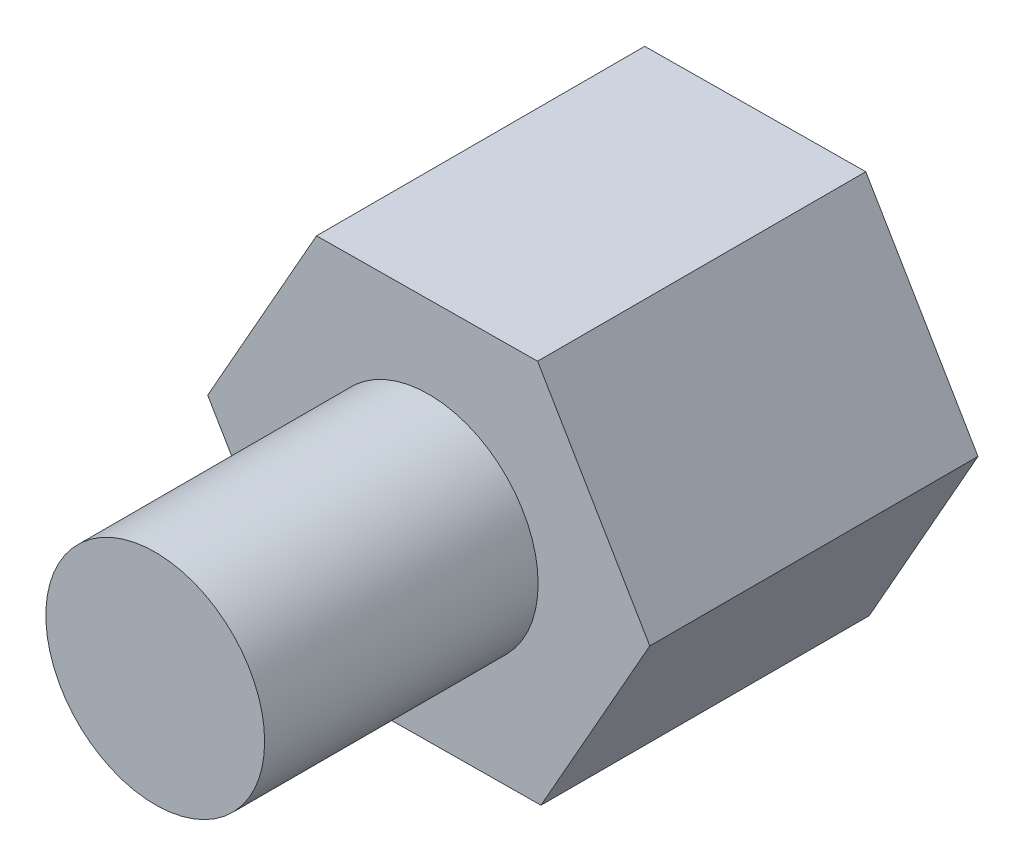
SolidWorks part; units mm, degrees
ref_plane "前视基准面" through (0, 0, 0) normal (0, 0, 1) x (1, 0, 0)
ref_plane "上视基准面" through (0, 0, 0) normal (0, 1, 0) x (1, 0, 0)
ref_plane "右视基准面" through (0, 0, 0) normal (1, 0, 0) x (0, 0, -1)
sketch "草图1" plane through (0, 0, 0) normal (0, 0, 1) x (1, 0, 0)
  line L1 (2.0515, -3.4821) -> (4.0413, 0.0356)
  line L2 (4.0413, 0.0356) -> (1.9898, 3.5177)
  line L3 (1.9898, 3.5177) -> (-2.0515, 3.4821)
  line L4 (-2.0515, 3.4821) -> (-4.0413, -0.0356)
  line L5 (-4.0413, -0.0356) -> (-1.9898, -3.5177)
  line L6 (-1.9898, -3.5177) -> (2.0515, -3.4821)
  circle A0 centre (0, 0) radius 3.5 construction
  circle A1 centre (0, 0) radius 2
extrude "凸台-拉伸1" add sketch "草图1" along normal blind 6
sketch "草图3" plane through (0, 0, 6) normal (0, 0, 1) x (1, 0, 0)
  circle A0 centre (0, 0) radius 2
extrude "凸台-拉伸2" add sketch "草图3" along normal blind 5 separate body
